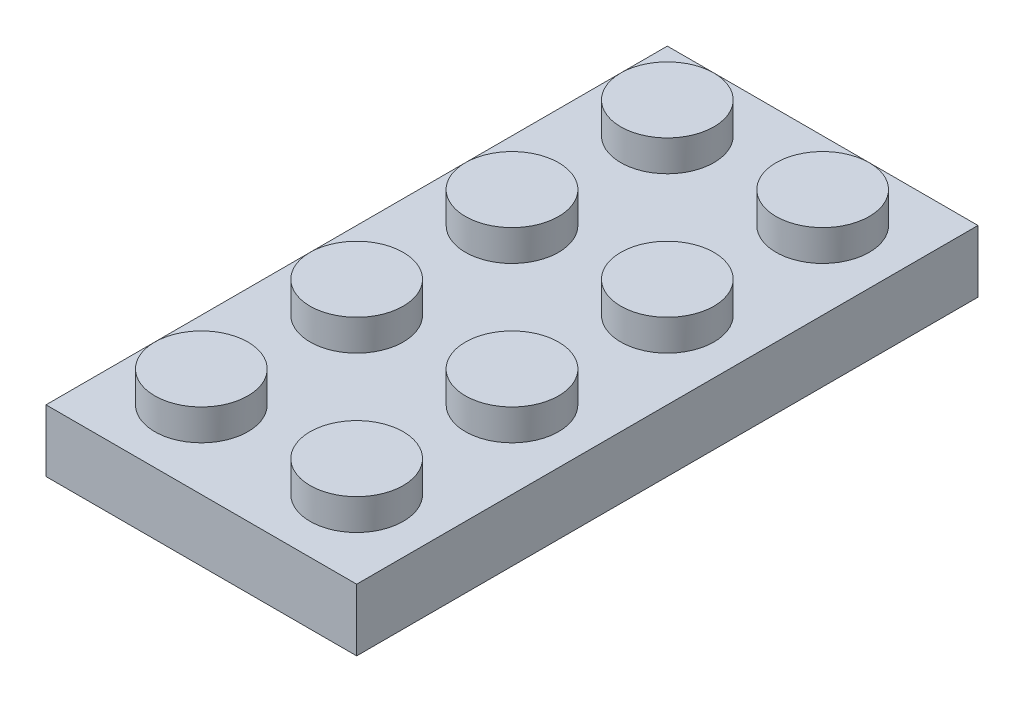
SolidWorks part; units mm, degrees
ref_plane "Front Plane" through (0, 0, 0) normal (0, 0, 1) x (1, 0, 0)
ref_plane "Top Plane" through (0, 0, 0) normal (0, 1, 0) x (1, 0, 0)
ref_plane "Right Plane" through (0, 0, 0) normal (1, 0, 0) x (0, 0, -1)
sketch "Sketch1" plane through (0, 0, 0) normal (0, 1, 0) x (1, 0, 0)
  line L1 (0, 0) -> (16, 0)
  line L2 (0, 0) -> (0, 32)
  line L3 (0, 32) -> (16, 32)
  line L4 (16, 0) -> (16, 32)
  dimension "D1" = 16
  dimension "D2" = 32
extrude "Boss-Extrude1" add sketch "Sketch1" along normal blind 3.2
sketch "Sketch2" plane through (0, 3.2, 0) normal (0, 1, 0) x (1, 0, 0)
  line L0 (8, 0) -> (8, 32) construction
  line L1 (0, 0) -> (16, 0) construction
  line L2 (16, 32) -> (0, 32) construction
  line L3 (16, 0) -> (16, 4) construction
  line L4 (16, 0) -> (16, 32) construction
  line L5 (16, 4) -> (12, 4) construction
  circle A0 centre (12, 4) radius 2.4
  dimension "D3" = 4.8
  dimension "D1" = 4
  dimension "D2" = 4
extrude "Boss-Extrude2" add sketch "Sketch2" along normal blind 1.6
pattern_linear "LPattern1" count 2 spacing 8 along (-1, 0, 0) count 4 spacing 8 along (0, 0, -1) of "Boss-Extrude2"
shell "Shell1" thickness 1.6
